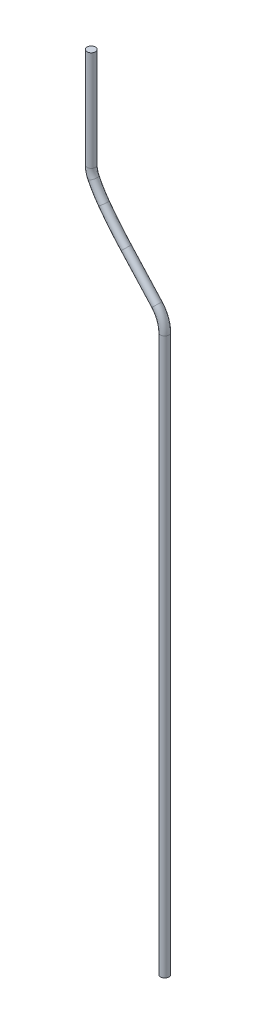
SolidWorks part; units mm, degrees
ref_plane "前视基准面" through (0, 0, 0) normal (0, 0, 1) x (1, 0, 0)
ref_plane "上视基准面" through (0, 0, 0) normal (0, 1, 0) x (1, 0, 0)
ref_plane "右视基准面" through (0, 0, 0) normal (1, 0, 0) x (0, 0, -1)
sketch "草图1" plane through (0, 0, 0) normal (0, 0, 1) x (1, 0, 0)
  line L0 (-132.24, 1375.12) -> (-132.24, 1195.0252)
  line L1 (0, 1000) -> (0, 0)
  arc A0 (-14.2211, 1036.9064) -> (0, 1000) centre (-55, 1000) cw
  arc A1 (-128.1922, 1177.4912) -> (-109.64, 1146.79) centre (51.5687, 1265.1613) ccw
  arc A2 (-109.64, 1146.79) -> (-69.4889, 1097.7629) centre (373.986, 1501.9039) ccw
  arc A3 (-69.4889, 1097.7629) -> (-14.2211, 1036.9064) centre (-17760.172, -15023.8503) cw
  arc A4 (-128.1922, 1177.4912) -> (-132.24, 1195.0252) centre (-92.24, 1195.0252) cw
  point P9 (0, 0)
  point P13 (0, 0)
  point P14 (0, 0)
  point P15 (0, 0)
  point P18 (-132.24, 1186.33)
  dimension "D2" = 200
  dimension "D3" = 600
  dimension "D5" = 188.79
  dimension "D8" = 55
  dimension "D11" = 40
  dimension "D1" = 132.24
  dimension "D4" = 1000
  dimension "D6" = 40.1511
  dimension "D7" = 375.12
  dimension "D9" = 39.54
  dimension "D10" = 22.6
sketch "草图2" plane through (0, 0, 0) normal (0, 1, 0) x (1, 0, 0)
  circle A0 centre (0, 0) radius 7.5
  dimension "D1" = 15
sweep "扫描1" add profiles "草图2" path "草图1"
